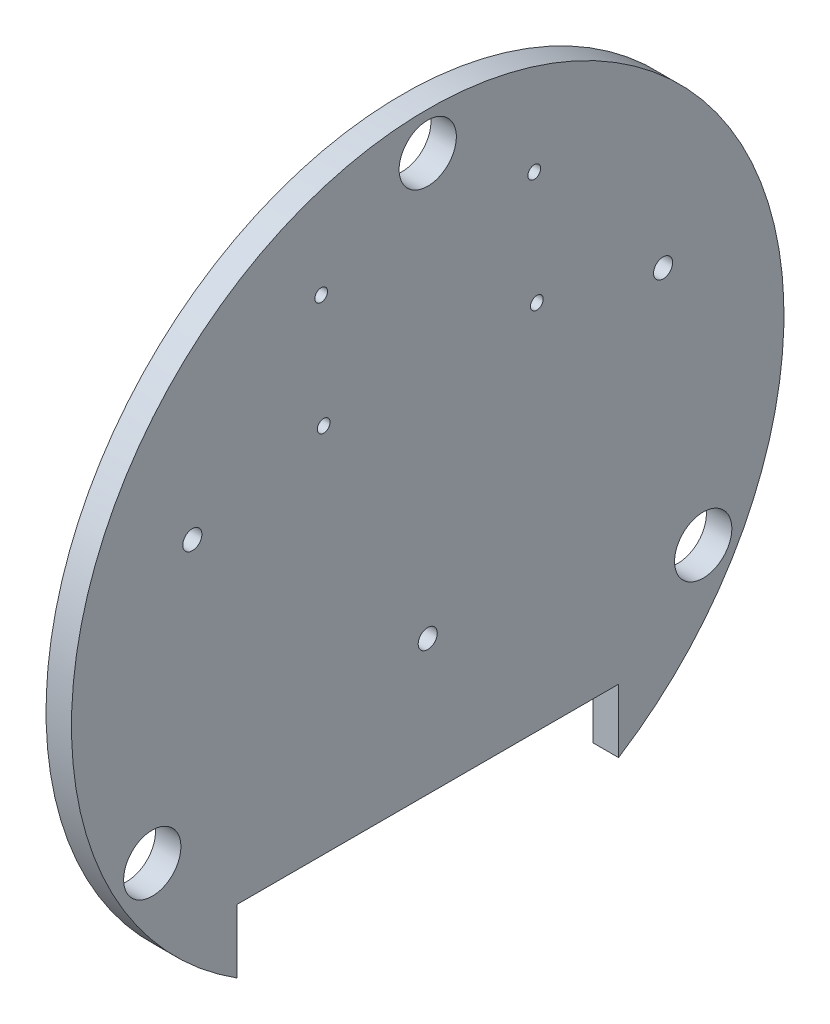
SolidWorks part; units mm, degrees
ref_plane "Ebene vorne" through (0, 0, 0) normal (0, 0, 1) x (1, 0, 0)
ref_plane "Ebene oben" through (0, 0, 0) normal (0, 1, 0) x (1, 0, 0)
ref_plane "Ebene rechts" through (0, 0, 0) normal (1, 0, 0) x (0, 0, -1)
sketch "Sketch1" plane through (0, 0, 0) normal (1, 0, 0) x (0, 0, -1)
  circle A0 centre (0, 0) radius 56
  dimension "D1" = 112
extrude "Boss-Extrude1" add sketch "Sketch1" along normal blind 4
sketch "Sketch2" plane through (0, 0, 0) normal (-1, 0, 0) x (0, 0, 1)
  circle A0 centre (0, 50) radius 4.5
  circle A1 centre (43.3013, -25) radius 4.5
  circle A2 centre (-43.3013, -25) radius 4.5
  point P9 (0, 0)
  dimension "D1" = 9
  dimension "D2" = 50
  dimension "D3" = 3
extrude "Cut-Extrude1" cut sketch "Sketch2" against normal through all
sketch "Sketch3" plane through (0, 0, 0) normal (-1, 0, 0) x (0, 0, 1)
  line L0 (-30, -47.2864) -> (-30, -37.2864)
  line L1 (0, 56) -> (0, -56) construction
  line L2 (30, -47.2864) -> (30, -37.2864)
  line L3 (-30, -37.2864) -> (30, -37.2864)
  circle A0 centre (0, 0) radius 56 construction
  arc A2 (-30, -47.2864) -> (30, -47.2864) centre (0, 0) ccw
  dimension "D1" = 10
  dimension "D2" = 60
extrude "Cut-Extrude2" cut sketch "Sketch3" against normal through all
sketch "Sketch4" plane through (4, 0, 0) normal (1, 0, 0) x (0, 0, -1)
  line L0 (0, 56) -> (0, -40.0081) construction
  circle A0 centre (-16.75, 39.0587) radius 1
  circle A1 centre (16.75, 39.0587) radius 1
  circle A2 centre (17.1527, 21.0632) radius 1
  circle A3 centre (-16.3473, 21.0632) radius 1
  circle A4 centre (-37, 15.8844) radius 1.5
  circle A5 centre (0, -16.0708) radius 1.5
  circle A6 centre (37, 15.8844) radius 1.5
  arc A7 (30, -47.2864) -> (-30, -47.2864) centre (0, 0) ccw construction
  circle A8 centre (0, -16.0708) radius 1.5 construction
  point P27 (0, 0)
  point P28 (0, 0)
  dimension "D1" = 2
  dimension "D2" = 3
extrude "Cut-Extrude3" cut sketch "Sketch4" against normal through all
